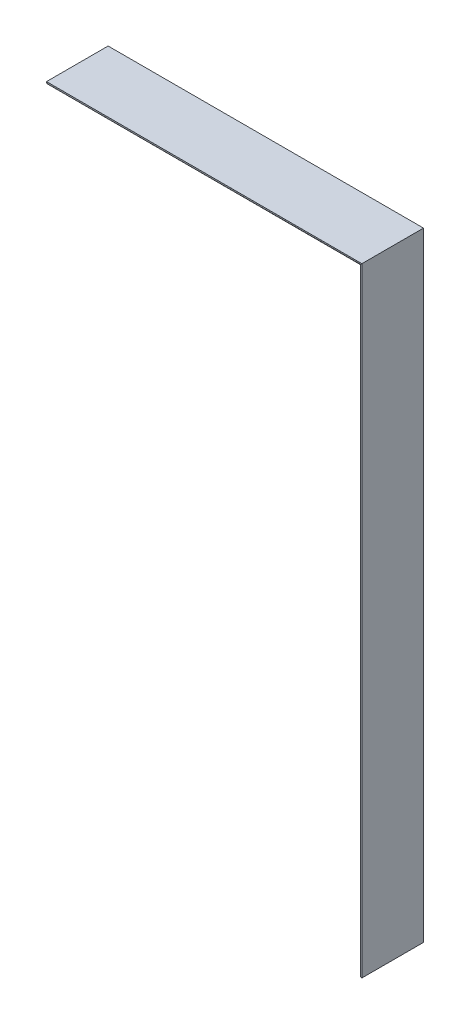
SolidWorks part; units mm, degrees
material "Fundición gris (SN)"
ref_plane "Alzado" through (0, 0, 0) normal (0, 0, 1) x (1, 0, 0)
ref_plane "Planta" through (0, 0, 0) normal (0, 1, 0) x (1, 0, 0)
ref_plane "Vista lateral" through (0, 0, 0) normal (1, 0, 0) x (0, 0, -1)
sketch "Croquis1" plane through (0, 0, 0) normal (0, 0, 1) x (1, 0, 0)
  line L0 (0, 0) -> (-260, 0)
  line L1 (0, 0) -> (0, -510)
  dimension "D1" = 260
  dimension "D2" = 510
other "Hierro angular 2 X 2 X 0.125(1)"
ref_plane "Plano1" through (0, 0, 0) normal (-1, 0, 0) x (0, -1, 0)
sketch "Sketch1" plane through (0, 0, 0) normal (-1, 0, 0) x (0, -1, 0)
  line L0 (0, 0) -> (0, 50.8)
  line L1 (0, 50.8) -> (0.0051, 50.8)
  line L2 (3.175, 47.6301) -> (3.175, 7.9375)
  line L3 (7.9375, 3.175) -> (47.6301, 3.175)
  line L4 (50.8, 0.0051) -> (50.8, 0)
  line L5 (50.8, 0) -> (0, 0)
  arc A0 (50.8, 0.0051) -> (47.6301, 3.175) centre (47.6301, 0.0051) ccw
  arc A1 (0.0051, 50.8) -> (3.175, 47.6301) centre (0.0051, 47.6301) cw
  arc A2 (7.9375, 3.175) -> (3.175, 7.9375) centre (7.9375, 7.9375) cw
  point P10 (25.4, 0)
  point P14 (0, 25.4)
  point P15 (3.175, 25.4)
  point P16 (25.4, 3.175)
  point P17 (3.175, 50.8)
  point P18 (50.8, 3.175)
  point P19 (0, 0)
  dimension "D2" = 0.0051
  dimension "Radius_1" = 4.7625
  dimension "D1" = 3.175
  dimension "H_leg" = 50.8
